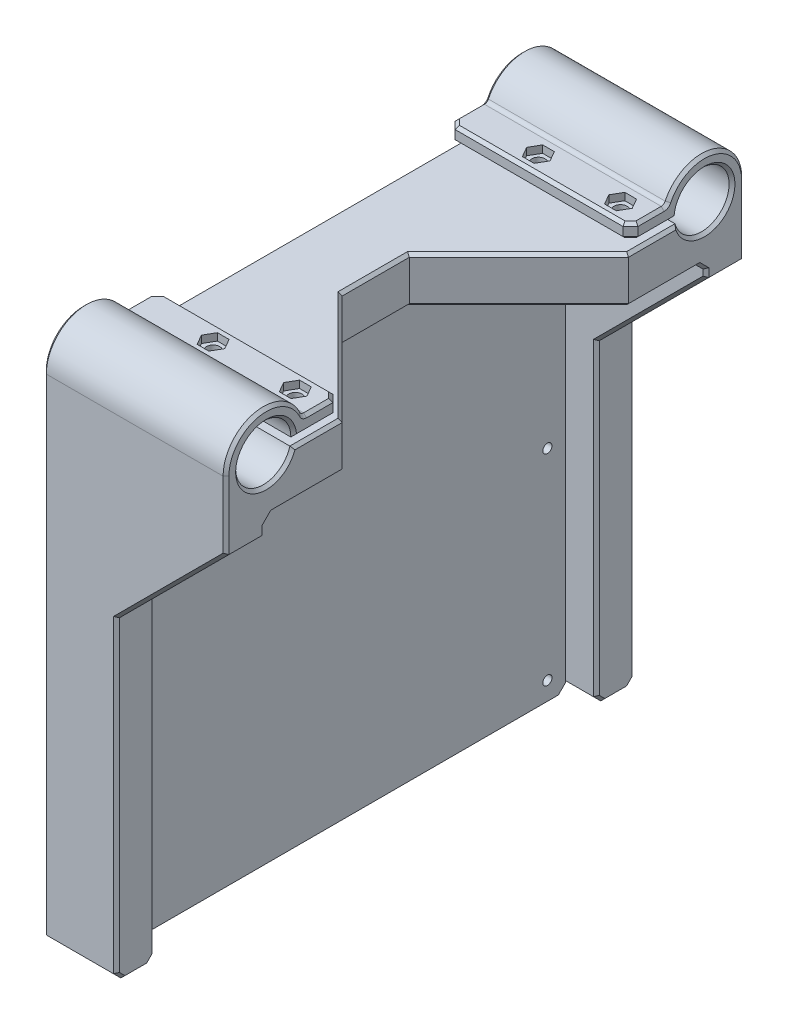
SolidWorks part; units mm, degrees
ref_plane "Front" through (0, 0, 0) normal (0, 0, 1) x (1, 0, 0)
ref_plane "Top" through (0, 0, 0) normal (0, 1, 0) x (1, 0, 0)
ref_plane "Right" through (0, 0, 0) normal (1, 0, 0) x (0, 0, -1)
sketch "Sketch1" plane through (0, 0, 0) normal (1, 0, 0) x (0, 0, -1)
  line L0 (60, 0) -> (-60, 0) construction
  circle A0 centre (-60, 0) radius 7.55
  circle A1 centre (-60, 0) radius 11
  circle A2 centre (60, 0) radius 7.55
  circle A3 centre (60, 0) radius 11
  point P7 (0, 0)
  dimension "D1" = 15.1
  dimension "D2" = 22
  dimension "D3" = 120
extrude "Boss-Extrude1" add sketch "Sketch1" along normal blind 50
sketch "Sketch4" plane through (0, 0, 0) normal (1, 0, 0) x (0, 0, -1)
  line L0 (60.4, -135.4) -> (60.4, -14.6) construction
  line L1 (60, -135) -> (-60, -135) construction
  line L2 (60, -135) -> (60, -15) construction
  line L3 (60, -15) -> (-60, -15) construction
  line L4 (-60, -135) -> (-60, -15) construction
  line L5 (60, -135) -> (-60, -15) construction
  line L6 (60, -15) -> (-60, -135) construction
  line L7 (60.4, -14.6) -> (-60.4, -14.6) construction
  line L8 (-60.4, -135.4) -> (-60.4, -14.6) construction
  line L9 (60.4, -135.4) -> (-60.4, -135.4) construction
  line L10 (-50, -135) -> (-50, -25)
  line L11 (-50, -25) -> (50, -25)
  line L12 (50, -25) -> (50, -135)
  line L13 (50, -135) -> (71, -135)
  line L14 (71, -135) -> (71, 0)
  line L15 (-50, -135) -> (-71, -135)
  line L16 (-71, -135) -> (-71, 0)
  line L17 (-49.1833, -2) -> (49.1833, -2)
  circle A1 centre (60, 0) radius 11 construction
  arc A2 (-49.1833, -2) -> (-71, 0) centre (-60, 0) cw
  arc A3 (71, 0) -> (49.1833, -2) centre (60, 0) cw
  circle A4 centre (-60, 0) radius 11 construction
  point P0 (0, -75)
  point P18 (0, -25)
  dimension "D1" = 120
  dimension "D2" = 75
  dimension "D4" = 10
  dimension "D5" = 10
  dimension "D6" = 2
  dimension "D3" = 0.4
extrude "Boss-Extrude3" add sketch "Sketch4" along normal up to surface (50 mm away) up to face at (50, 0, 49)
sketch "Sketch12" plane through (0, 0, 0) normal (-1, 0, 0) x (0, 0, 1)
  line L1 (-60.4, -14.6) -> (60.4, -14.6)
  line L2 (-60.4, -14.6) -> (-60.4, -135.4)
  line L3 (-60.4, -135.4) -> (60.4, -135.4)
  line L4 (60.4, -14.6) -> (60.4, -135.4)
extrude "Cut-Extrude3" cut sketch "Sketch12" against normal up to surface (44 mm away) from offset 6 up to face at (50, -57.0092, 0) offset against normal yes
hole_wizard "CSK for M3 Flat Head Machine Screw1" positions "Sketch6" profile "Sketch8" countersink size "M3" standard "ANSI Metric" end condition through all
sketch "Sketch6" plane through (0, 0, 0) normal (-1, 0, 0) x (0, 0, 1)
  line L1 (55, -130) -> (-55, -130) construction
  line L2 (55, -130) -> (55, -20) construction
  line L3 (55, -20) -> (-55, -20) construction
  line L4 (-55, -130) -> (-55, -20) construction
  line L5 (55, -130) -> (-55, -20) construction
  line L6 (55, -20) -> (-55, -130) construction
  line L7 (-60, -135) -> (60, -15) construction
  point P0 (-55, -130)
  point P2 (-55, -75)
  point P4 (-55, -20)
  point P6 (0, -20)
  point P8 (55, -20)
  point P10 (55, -75)
  point P12 (55, -130)
  point P15 (0, -75)
  point P79 (-55, -75)
  point P80 (55, -75)
  point P81 (0, -20)
  dimension "D1" = 110
sketch "Sketch8" plane through (0, -130, -55) normal (0, 1, 0) x (0, 0, 1)
  line L0 (0, 0) -> (0, 50)
  line L1 (0, 50) -> (1.8, 50)
  line L2 (1.8, 50) -> (1.8, 1.35)
  line L3 (1.8, 1.35) -> (3.15, 0)
  line L5 (3.15, 0) -> (0, 0)
  line L6 (-1.8, 1.35) -> (-3.15, 0) construction
  line L11 (0, -6.35) -> (0, 107.95) construction
  dimension "Thru Hole Dia." = 3.6
  dimension "Thru Hole Depth" = 50
  dimension "Near C'Sink Dia." = 6.3
  dimension "Near C'Sink Angle" = 90
sketch "Sketch13" plane through (0, -2, 0) normal (0, 1, 0) x (1, 0, 0)
  line L0 (50, 49.1833) -> (50, 39.1833) construction
  line L1 (50, 49.1833) -> (50, -49.1833) construction
  line L2 (50, 39.1833) -> (20, 9.1833)
  line L3 (20, 9.1833) -> (20, -9.1833)
  line L4 (20, -9.1833) -> (50, -39.1833)
  line L5 (50, -39.1833) -> (50, 39.1833)
  line L7 (0, 60) -> (0, -60) construction
  point P6 (50, 0)
  point P9 (20, 0)
  dimension "D1" = 45
  dimension "D2" = 10
  dimension "D3" = 20
extrude "Cut-Extrude4" cut sketch "Sketch13" against normal up to surface (12.6 mm away) up to face at (28, -14.6, 0)
sketch "Sketch14" plane through (6, 0, 0) normal (1, 0, 0) x (0, 0, -1)
  line L1 (-60, -15) -> (60, -15)
  line L2 (-60, -15) -> (-60, -135)
  line L3 (-60, -135) -> (60, -135)
  line L4 (60, -15) -> (60, -135)
extrude "Boss-Extrude7" add sketch "Sketch14" along normal blind 6 separate body
chamfer "Chamfer2" distance 2 angle 45 4 edges at (9, -15, 60) (9, -15, -60) (9, -135, 60) (9, -135, -60)
hole_wizard "M3x0.5 Tapped Hole1" positions "Sketch15" profile "Sketch16" tap size "M3x0.5" standard "ANSI Metric" end condition through all
sketch "Sketch15" plane through (12, 0, 0) normal (1, 0, 0) x (0, 0, -1)
  point P0 (-55, -20)
  point P2 (-55, -75)
  point P4 (-55, -130)
  point P6 (0, -20)
  point P8 (55, -20)
  point P10 (55, -75)
  point P12 (55, -130)
sketch "Sketch16" plane through (12, -20, 55) normal (0, 1, 0) x (0, 0, -1)
  line L0 (0, 0) -> (0, 12)
  line L1 (0, 12) -> (1.25, 12)
  line L2 (1.25, 12) -> (1.25, 0)
  line L5 (1.25, 0) -> (0, 0)
  line L11 (0, -6.35) -> (0, 107.95) construction
  dimension "Thru Tap Drill Dia." = 2.5
  dimension "Thru Tap Drill Depth" = 12
cosmetic thread "Hole Thread1" parameters "D2"=3
cosmetic thread "Hole Thread2" parameters "D2"=3
cosmetic thread "Hole Thread3" parameters "D2"=3
cosmetic thread "Hole Thread4" parameters "D2"=3
cosmetic thread "Hole Thread5" parameters "D2"=3
cosmetic thread "Hole Thread6" parameters "D2"=3
cosmetic thread "Hole Thread7" parameters "D2"=3
sketch "Sketch17" plane through (0, 0, -60.4) normal (0, 0, 1) x (1, 0, 0)
  line L0 (50, -18.6) -> (20, -48.6)
  line L1 (50, -14.6) -> (50, -135) construction
  line L2 (20, -14.6) -> (20, -2) construction
  line L3 (50, -18.6) -> (50, -135)
  line L4 (50, -135) -> (20, -135)
  line L5 (50, -135) -> (0, -135) construction
  line L6 (20, -48.6) -> (20, -135)
  dimension "D1" = 4
  dimension "D2" = 45
extrude "Cut-Extrude5" cut sketch "Sketch17" against normal through all both and the other way through all
sketch "Sketch19" plane through (50, 0, 0) normal (1, 0, 0) x (0, 0, -1)
  line L0 (-39.1833, -2) -> (-49.1833, -2) construction
  line L1 (-52.7197, -2) -> (52.7197, -2)
  line L2 (-52.7197, -2) -> (-52.7197, 0)
  line L3 (-52.7197, 0) -> (52.7197, 0)
  line L4 (52.7197, -2) -> (52.7197, 0)
  circle A0 centre (-60, 0) radius 7.55 construction
  circle A2 centre (60, 0) radius 7.55 construction
  dimension "D1" = 2
extrude "Cut-Extrude6" cut sketch "Sketch19" against normal through all both and the other way through all
sketch "Sketch20" plane through (50, 0, 0) normal (1, 0, 0) x (0, 0, -1)
  line L0 (52.45, 0) -> (49, 0) construction
  line L1 (-49.753, 0) -> (-39.753, 0)
  line L2 (-49.753, 0) -> (-49.753, 4)
  line L3 (-49.753, 4) -> (-39.753, 4)
  line L4 (-39.753, 0) -> (-39.753, 4)
  line L5 (49.753, 0) -> (39.753, 0)
  line L6 (49.753, 0) -> (49.753, 4)
  line L7 (49.753, 4) -> (39.753, 4)
  line L8 (39.753, 0) -> (39.753, 4)
  arc A1 (-49, 0) -> (-71, 0) centre (-60, 0) ccw construction
  arc A2 (71, 0) -> (49, 0) centre (60, 0) ccw construction
  point P9 (0, 0)
  point P13 (0, 0)
  point P14 (-52.4828, -0.6701)
  point P15 (-49.7623, 4.0237)
  point P19 (-50.6182, 5.7431)
  point P21 (0, 0)
  point P25 (55.2319, -1.439)
  dimension "D1" = 4
  dimension "D2" = 10
extrude "Boss-Extrude9" add sketch "Sketch20" against normal up to surface (50 mm away) up to face at (0, -130, -51.85)
sketch "Sketch21" plane through (0, 4, 0) normal (0, 1, 0) x (1, 0, 0)
  line L0 (0, 39.753) -> (0, 49.753) construction
  line L1 (45.7043, 44.528) -> (44.1021, 47.303)
  line L2 (44.1021, 47.303) -> (40.8979, 47.303)
  line L3 (40.8979, 47.303) -> (39.2957, 44.528)
  line L4 (39.2957, 44.528) -> (40.8979, 41.753)
  line L5 (40.8979, 41.753) -> (44.1021, 41.753)
  line L6 (44.1021, 41.753) -> (45.7043, 44.528)
  line L7 (23.2043, 44.528) -> (21.6021, 47.303)
  line L8 (21.6021, 47.303) -> (18.3979, 47.303)
  line L9 (18.3979, 47.303) -> (16.7957, 44.528)
  line L10 (16.7957, 44.528) -> (18.3979, 41.753)
  line L11 (18.3979, 41.753) -> (21.6021, 41.753)
  line L12 (21.6021, 41.753) -> (23.2043, 44.528)
  line L13 (23.2043, -44.528) -> (21.6021, -41.753)
  line L14 (21.6021, -41.753) -> (18.3979, -41.753)
  line L15 (18.3979, -41.753) -> (16.7957, -44.528)
  line L16 (16.7957, -44.528) -> (18.3979, -47.303)
  line L17 (18.3979, -47.303) -> (21.6021, -47.303)
  line L18 (21.6021, -47.303) -> (23.2043, -44.528)
  line L19 (45.7043, -44.528) -> (44.1021, -41.753)
  line L20 (44.1021, -41.753) -> (40.8979, -41.753)
  line L21 (40.8979, -41.753) -> (39.2957, -44.528)
  line L22 (39.2957, -44.528) -> (40.8979, -47.303)
  line L23 (40.8979, -47.303) -> (44.1021, -47.303)
  line L24 (44.1021, -47.303) -> (45.7043, -44.528)
  line L25 (50, 39.753) -> (42.5, 39.753) construction
  line L26 (50, 39.753) -> (50, 44.528) construction
  line L27 (50, 44.528) -> (42.5, 44.528) construction
  line L28 (42.5, 39.753) -> (42.5, 44.528) construction
  line L29 (0, 39.753) -> (20, 39.753) construction
  line L30 (0, 39.753) -> (0, 44.528) construction
  line L31 (0, 44.528) -> (20, 44.528) construction
  line L32 (20, 39.753) -> (20, 44.528) construction
  line L33 (0, 39.753) -> (50, 39.753) construction
  line L35 (0, -39.753) -> (20, -39.753) construction
  line L36 (0, -39.753) -> (0, -44.528) construction
  line L37 (0, -44.528) -> (20, -44.528) construction
  line L38 (20, -39.753) -> (20, -44.528) construction
  line L39 (50, -39.753) -> (42.5, -39.753) construction
  line L40 (50, -39.753) -> (50, -44.528) construction
  line L41 (50, -44.528) -> (42.5, -44.528) construction
  line L42 (42.5, -39.753) -> (42.5, -44.528) construction
  circle A0 centre (42.5, 44.528) radius 2.775 construction
  circle A1 centre (20, 44.528) radius 2.775 construction
  circle A2 centre (20, -44.528) radius 2.775 construction
  circle A3 centre (42.5, -44.528) radius 2.775 construction
  dimension "D1" = 5.55
  dimension "D2" = 2
  dimension "D3" = 7.5
  dimension "D4" = 20
extrude "Cut-Extrude7" cut sketch "Sketch21" against normal blind 2
hole_wizard "CSK for M3 Flat Head Machine Screw2" positions "Sketch22" profile "Sketch24" countersink size "M3" standard "ANSI Metric" end condition through all
sketch "Sketch22" plane through (0, -14.6, 0) normal (0, -1, 0) x (-1, 0, 0)
  point P0 (-20, 44.528)
  point P2 (-42.5, 44.528)
  point P4 (-20, -44.528)
  point P6 (-42.5, -44.528)
sketch "Sketch24" plane through (20, -14.6, -44.528) normal (1, 0, 0) x (0, 0, -1)
  line L0 (0, 0) -> (0, 25.6)
  line L1 (0, 25.6) -> (1.8, 25.6)
  line L2 (1.8, 25.6) -> (1.8, 1.35)
  line L3 (1.8, 1.35) -> (3.15, 0)
  line L5 (3.15, 0) -> (0, 0)
  line L6 (-1.8, 1.35) -> (-3.15, 0) construction
  line L11 (0, -6.35) -> (0, 107.95) construction
  dimension "Thru Hole Dia." = 3.6
  dimension "Thru Hole Depth" = 25.6
  dimension "Near C'Sink Dia." = 6.3
  dimension "Near C'Sink Angle" = 90
chamfer "Chamfer6" distance 2 angle 45 4 edges at (0, 2, -39.753) (50, 2, -39.753) (0, 2, 39.753) (50, 2, 39.753)
chamfer "Chamfer3" distance 2 angle 45 10 edges at (3, -135, 50) (3, -25, 50) (3, -25, -50) (3, -135, -50) (28, -14.6, -60.4) (28, -14.6, 60.4) (10, -135, -71) (13, -135, -60.4) (10, -135, 71) (13, -135, 60.4)
fillet "Fillet2" radius 1.2 2 edges at (25, 4, 49.753) (25, 4, -49.753)
chamfer "Chamfer5" distance 0.8 angle 45 85 edges at (0, 10.7345, -62.4022) (50, -2, 45.9515) (20, -2, 0) (50, -2, -45.9515) (0, -2, 0) (0, 10.7345, 62.4022) (0, -66.5, 71) (20, -134, 70) (0, -134, 70) (0, -135, 60.5) (6, -134, 51) (0, -134, 51) (6, -80, 50) (0, -80, 50) (6, -26, 49) (0, -26, 49) (6, -25, 0) (0, -25, 0) (6, -26, -49) (0, -26, -49) (6, -80, -50) (0, -80, -50) (6, -134, -51) (0, -134, -51) (0, -135, -60.5) (20, -134, -70) (0, -134, -70) (0, -66.5, -71) (0, 1.0091, -67.4823) (50, 1.0091, -67.4823) (0, 1.0091, 67.4823) (50, 1.0091, 67.4823) (50, -9.3, 71) (50, 10.7345, 62.4022) (35, -2, 24.1833) (35, -2, -24.1833) (50, 10.7345, -62.4022) (35, -33.6, 71) (20, -90.8, 71) (20, -135, 65.7) (20, -134, 61.4) (20, -90.8, 60.4) (35, -33.6, 60.4) (50, -17.6, 60.4) (50, -15.6, 59.4) (50, -14.6, 48.7917) (35, -14.6, 24.1833) (20, -14.6, 0) (35, -14.6, -24.1833) (50, -9.3, -71) (35, -33.6, -71) (50, -14.6, -48.7917) (50, -15.6, -59.4) (50, -17.6, -60.4) (35, -33.6, -60.4) (20, -90.8, -60.4) (20, -90.8, -71) (20, -135, -65.7) (20, -134, -61.4) (6, -135, -57.2) (6, -135, 57.2) (50, 4, 45.3584) (0, 4.1866, 49.6064) (50, 4.1866, 49.6064) (50, 4, -45.3584) (0, 4.1866, -49.6064) (50, 4.1866, -49.6064) (0, 4, -45.3584) (1, 4, -40.753) (25, 4, -39.753) (49, 4, -40.753) (0, 4, 45.3584) (1, 4, 40.753) (25, 4, 39.753) (49, 4, 40.753) (1, 0, -40.753) (0, 0, -47.1015) (0, 0, 47.1015) (1, 0, 40.753) (25, 0, -39.753) (49, 0, -40.753) (50, 0, -47.1015) (25, 0, 39.753) (49, 0, 40.753) (50, 0, 47.1015)
